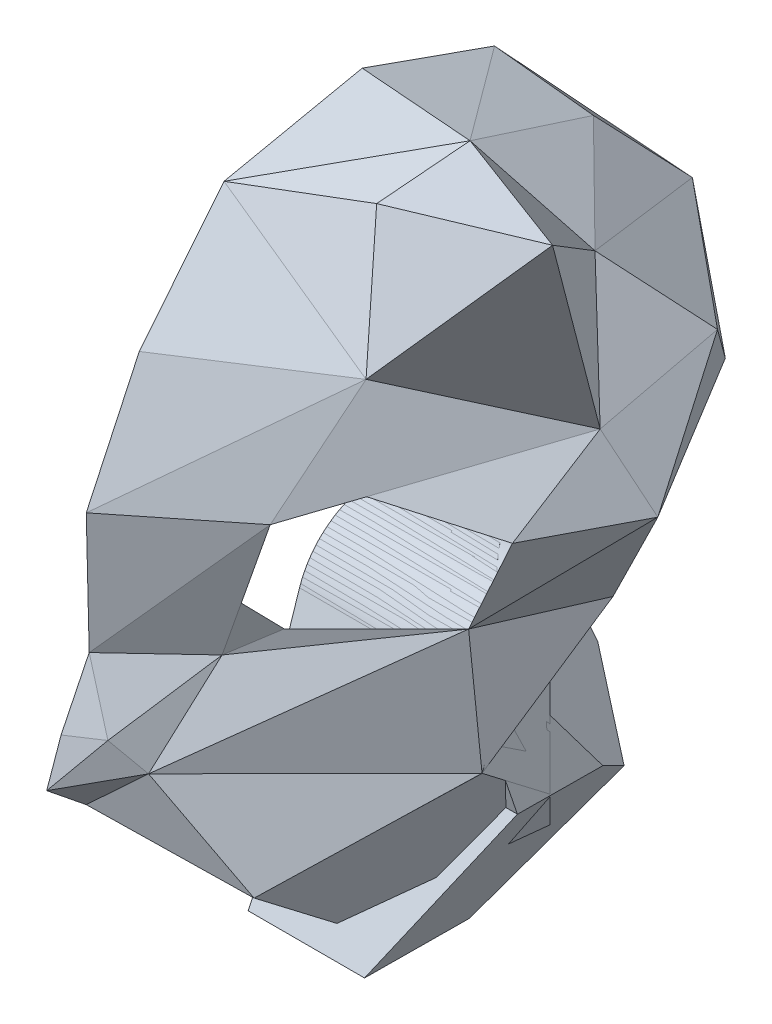
SolidWorks part; units mm, degrees
ref_plane "Front Plane" through (0, 0, 0) normal (0, 0, 1) x (1, 0, 0)
ref_plane "Top Plane" through (0, 0, 0) normal (0, 1, 0) x (1, 0, 0)
ref_plane "Right Plane" through (0, 0, 0) normal (1, 0, 0) x (0, 0, -1)
sketch "Front Pic" plane through (0, 0, 0) normal (0, 0, 1) x (1, 0, 0)
  line L0 (0, -457.2) -> (0, 457.2) construction
  line L1 (-457.2, 0) -> (457.2, 0) construction
  line L2 (-354.5768, -128.31) -> (79.4232, -128.31) construction
  point P4 (0, 0)
  point P8 (0, 0)
  dimension "D1" = 914.4
sketch "Front Sketch" plane through (0, 0, 0) normal (0, 0, 1) x (1, 0, 0)
  line L0 (0, 457.2) -> (-165.0753, 450.1039)
  line L1 (-165.0753, 450.1039) -> (-138.2224, 411.8242)
  line L2 (-138.2224, 411.8242) -> (-198.7843, 255.8487)
  line L3 (-198.7843, 255.8487) -> (-429.6051, 520.3785)
  line L4 (-429.6051, 520.3785) -> (-138.2224, 411.8242)
  line L5 (0, 457.2) -> (0, 259.8481)
  line L6 (0, -457.2) -> (0, 457.2) construction
  line L7 (0, 259.8481) -> (-198.7843, 255.8487)
  line L8 (-138.2224, 411.8242) -> (0, 414.6051)
  line L9 (-429.6051, 520.3785) -> (-381.0413, 202.1428)
  line L10 (-381.0413, 202.1428) -> (-198.7843, 255.8487)
  line L11 (-198.7843, 255.8487) -> (-150.7692, 92.9039)
  line L12 (-150.7692, 92.9039) -> (150.7692, 92.9039)
  line L13 (0, 92.9039) -> (0, 259.8481)
  line L14 (-150.7692, 92.9039) -> (-96.0877, -92.6643)
  line L15 (-96.0877, -92.6643) -> (0, -87.6822)
  line L16 (0, -87.6822) -> (0, 92.9039)
  line L17 (-150.7692, 92.9039) -> (-381.0413, 202.1428)
  line L18 (-381.0413, 202.1428) -> (-347.0618, 86.8295)
  line L19 (-347.0618, 86.8295) -> (-218.0815, 124.8362)
  line L20 (-347.0618, 86.8295) -> (-434.9799, 101.0648)
  line L21 (-434.9799, 101.0648) -> (-325.7476, -76.4377)
  line L22 (-325.7476, -76.4377) -> (-282.294, -55.0183)
  line L23 (-282.294, -55.0183) -> (-347.0618, 86.8295)
  line L24 (-325.7476, -76.4377) -> (-294.3404, -236.9902)
  line L25 (-294.3404, -236.9902) -> (-282.294, -55.0183)
  line L26 (-282.294, -55.0183) -> (-143.2329, -58.0087)
  line L27 (-143.2329, -58.0087) -> (-96.0877, -92.6643)
  line L28 (-71.7002, -214.569) -> (-282.294, -55.0183)
  line L29 (-143.2329, -58.0087) -> (-117.9524, -18.4637)
  line L30 (-96.0877, -92.6643) -> (0, -232.6592)
  line L31 (0, -232.6592) -> (0, -87.6822)
  line L32 (0, -232.6592) -> (0, -279.6939)
  line L33 (0, -279.6939) -> (-71.7002, -214.569)
  line L34 (-71.7002, -214.569) -> (-41.5067, -172.186)
  line L35 (-41.5067, -172.186) -> (41.5067, -172.186)
  line L36 (-71.7002, -214.569) -> (-294.3404, -236.9902)
  line L37 (-294.3404, -236.9902) -> (-172.0864, -350.6598)
  line L38 (-172.0864, -350.6598) -> (172.0864, -350.6598)
  line L39 (0, -350.6598) -> (0, -279.6939)
  line L40 (-434.9799, 101.0648) -> (-381.0413, 202.1428)
  line L41 (381.0413, 202.1428) -> (325.7476, 378.1651)
  line L42 (-143.2329, -350.6598) -> (-89.5204, -431.353)
  line L43 (-89.5204, -431.353) -> (89.5204, -431.353)
  line L44 (0, -431.353) -> (0, -350.6598)
  line L45 (-76.301, -431.353) -> (-51.5863, -391.0064)
  line L46 (-51.5863, -391.0064) -> (-37.7921, -431.353)
  line L47 (-117.9524, -350.6598) -> (-86.0432, -402.0403)
  line L48 (-86.0432, -402.0403) -> (-71.7002, -350.6598)
  line L49 (-233.2134, -293.825) -> (-122.2817, -456.0677)
  line L50 (-122.2817, -456.0677) -> (122.2817, -456.0677)
  line L51 (0, -456.0677) -> (0, -431.353)
  line L52 (233.2134, -293.825) -> (122.2817, -456.0677)
  line L53 (86.0432, -402.0403) -> (71.7002, -350.6598)
  line L54 (117.9524, -350.6598) -> (86.0432, -402.0403)
  line L55 (51.5863, -391.0064) -> (37.7921, -431.353)
  line L56 (76.301, -431.353) -> (51.5863, -391.0064)
  line L57 (143.2329, -350.6598) -> (89.5204, -431.353)
  line L58 (325.7476, 378.1651) -> (138.2224, 411.8242)
  line L59 (434.9799, 101.0648) -> (381.0413, 202.1428)
  line L60 (294.3404, -236.9902) -> (172.0864, -350.6598)
  line L61 (71.7002, -214.569) -> (294.3404, -236.9902)
  line L62 (71.7002, -214.569) -> (41.5067, -172.186)
  line L63 (0, -279.6939) -> (71.7002, -214.569)
  line L64 (96.0877, -92.6643) -> (0, -232.6592)
  line L65 (143.2329, -58.0087) -> (117.9524, -18.4637)
  line L66 (0, -456.0677) -> (89.5204, -431.353)
  line L67 (143.2329, -58.0087) -> (96.0877, -92.6643)
  line L68 (282.294, -55.0183) -> (143.2329, -58.0087)
  line L69 (294.3404, -236.9902) -> (282.294, -55.0183)
  line L70 (325.7476, -76.4377) -> (294.3404, -236.9902)
  line L71 (282.294, -55.0183) -> (347.0618, 86.8295)
  line L72 (325.7476, -76.4377) -> (282.294, -55.0183)
  line L73 (434.9799, 101.0648) -> (325.7476, -76.4377)
  line L74 (347.0618, 86.8295) -> (434.9799, 101.0648)
  line L75 (347.0618, 86.8295) -> (218.0815, 124.8362)
  line L76 (381.0413, 202.1428) -> (347.0618, 86.8295)
  line L77 (150.7692, 92.9039) -> (381.0413, 202.1428)
  line L78 (96.0877, -92.6643) -> (0, -87.6822)
  line L79 (150.7692, 92.9039) -> (96.0877, -92.6643)
  line L80 (198.7843, 255.8487) -> (150.7692, 92.9039)
  line L81 (381.0413, 202.1428) -> (198.7843, 255.8487)
  line L82 (429.6051, 520.3785) -> (381.0413, 202.1428)
  line L83 (138.2224, 411.8242) -> (0, 414.6051)
  line L84 (0, 259.8481) -> (198.7843, 255.8487)
  line L85 (429.6051, 520.3785) -> (138.2224, 411.8242)
  line L86 (198.7843, 255.8487) -> (429.6051, 520.3785)
  line L87 (138.2224, 411.8242) -> (198.7843, 255.8487)
  line L88 (165.0753, 450.1039) -> (138.2224, 411.8242)
  line L89 (0, 457.2) -> (165.0753, 450.1039)
  line L90 (-172.0864, -350.6598) -> (-71.7002, -214.569)
  line L91 (172.0864, -350.6598) -> (71.7002, -214.569)
  line L92 (-172.0864, -350.6598) -> (0, -279.6939)
  line L93 (-71.7002, -214.569) -> (-96.0877, -92.6643)
  line L94 (-96.0877, -92.6643) -> (-282.294, -55.0183)
  line L95 (0, -87.6822) -> (-150.7692, 92.9039)
  line L96 (0, 92.9039) -> (-198.7843, 255.8487)
  line L97 (-198.7843, 255.8487) -> (0, 414.6051)
  line L98 (0, 414.6051) -> (-165.0753, 450.1039)
  line L99 (-122.2817, -456.0677) -> (-89.5204, -431.353)
  line L100 (0, -456.0677) -> (-89.5204, -431.353)
  line L101 (-282.294, -55.0183) -> (-434.9799, 101.0648)
  line L102 (122.2817, -456.0677) -> (89.5204, -431.353)
  line L103 (282.294, -55.0183) -> (434.9799, 101.0648)
  line L104 (0, 414.6051) -> (165.0753, 450.1039)
  line L105 (198.7843, 255.8487) -> (0, 414.6051)
  line L106 (0, 92.9039) -> (198.7843, 255.8487)
  line L107 (0, -87.6822) -> (150.7692, 92.9039)
  line L108 (71.7002, -214.569) -> (96.0877, -92.6643)
  line L109 (96.0877, -92.6643) -> (282.294, -55.0183)
  line L110 (71.7002, -214.569) -> (282.294, -55.0183)
  line L111 (172.0864, -350.6598) -> (0, -279.6939)
  line L112 (-41.5067, -172.186) -> (0, -87.6822)
  line L113 (41.5067, -172.186) -> (0, -87.6822)
  line L114 (165.0753, 450.1039) -> (325.7476, 378.1651)
  line L115 (325.7476, 378.1651) -> (429.6051, 520.3785)
  line L116 (434.9799, 101.0648) -> (413.843, 275.5952)
  line L117 (413.843, 275.5952) -> (325.7476, 378.1651)
  line L118 (-434.9799, 101.0648) -> (-413.843, 275.5952)
  line L119 (-381.0413, 202.1428) -> (-325.7476, 378.1651)
  line L120 (-413.843, 275.5952) -> (-325.7476, 378.1651)
  line L121 (-325.7476, 378.1651) -> (-429.6051, 520.3785)
  line L122 (-165.0753, 450.1039) -> (-325.7476, 378.1651)
  line L123 (-325.7476, 378.1651) -> (-138.2224, 411.8242)
  point P60 (0, -172.186)
sketch "Side Pic" plane through (0, 0, 0) normal (1, 0, 0) x (0, 0, -1)
  line L0 (0, 0) -> (914.4, 0) construction
  line L2 (457.2, -457.2) -> (457.2, 457.2) construction
  line L3 (-402.7911, -837.6232) -> (-658.6062, -472.2814) construction
  point P4 (0, 0)
  point P8 (0, 0)
  point P9 (457.2, 0)
  dimension "D1" = 914.4
sketch "Side Sketch" plane through (0, 0, 0) normal (1, 0, 0) x (0, 0, -1)
  line L0 (0, -232.6592) -> (69.2409, -232.6592) construction
  line L1 (0, -456.0677) -> (498.8433, -456.0677) construction
  line L2 (0, 457.2) -> (534.3463, 457.2) construction
  line L3 (0, -87.6822) -> (131.8928, -87.6822) construction
  line L4 (0, -172.186) -> (90.4589, -172.186) construction
  line L5 (0, 520.3785) -> (0, 202.1428) construction
  line L6 (0, 520.3785) -> (383.7972, 520.3785) construction
  line L7 (69.2409, -232.6592) -> (90.4589, -189.1486)
  line L8 (90.4589, -189.1486) -> (118.3042, -186.9118)
  line L9 (118.3042, -186.9118) -> (148.2945, -199.1583)
  line L10 (148.2945, -199.1583) -> (127.5652, -272.936)
  line L11 (127.5652, -272.936) -> (69.2409, -232.6592)
  line L12 (69.2409, -232.6592) -> (118.3042, -186.9118)
  line L13 (90.4589, -189.1486) -> (131.8928, -87.6822)
  line L14 (131.8928, -87.6822) -> (232.8093, -58.1657)
  line L15 (232.8093, -58.1657) -> (118.3042, -186.9118)
  line L16 (148.2945, -199.1583) -> (290.6522, -152.5117)
  line L17 (290.6522, -152.5117) -> (232.8093, -58.1657)
  line L18 (232.8093, -58.1657) -> (277.7966, -16.2187)
  line L19 (277.7966, -16.2187) -> (237.7872, 11.4104)
  line L20 (237.7872, 11.4104) -> (232.8093, -58.1657)
  line L21 (277.7966, -16.2187) -> (408.2382, 38.4623)
  line L22 (408.2382, 38.4623) -> (290.6522, -152.5117)
  line L23 (127.5652, -272.936) -> (206.0473, -321.2589)
  line L24 (206.0473, -321.2589) -> (290.6522, -152.5117)
  line L25 (206.0473, -321.2589) -> (414.9631, -214.8375)
  line L26 (414.9631, -214.8375) -> (290.6522, -152.5117)
  line L27 (290.6522, -152.5117) -> (576.9901, -43.4043)
  line L28 (576.9901, -43.4043) -> (408.2382, 38.4623)
  line L29 (414.9631, -214.8375) -> (378.4644, -119.0513)
  line L30 (408.2382, 38.4623) -> (534.3463, 67.7772)
  line L31 (534.3463, 67.7772) -> (576.9901, -43.4043)
  line L32 (576.9901, -43.4043) -> (757.3012, -1.4894)
  line L33 (757.3012, -1.4894) -> (712.1006, 116.3584)
  line L34 (712.1006, 116.3584) -> (534.3463, 67.7772)
  line L35 (408.2382, 38.4623) -> (414.9454, 182.3846)
  line L36 (414.9454, 182.3846) -> (543.3881, 217.4886)
  line L37 (543.3881, 217.4886) -> (534.3463, 67.7772)
  line L38 (543.3881, 217.4886) -> (662.4014, 250.0155)
  line L39 (662.4014, 250.0155) -> (712.1006, 116.3584)
  line L40 (131.8928, -87.6822) -> (127.5652, 100.5606)
  line L41 (127.5652, 100.5606) -> (246.365, 119.1618)
  line L42 (246.365, 119.1618) -> (237.7872, 11.4104)
  line L43 (246.365, 119.1618) -> (414.9454, 182.3846)
  line L44 (127.5652, 100.5606) -> (205.7326, 268.0226)
  line L45 (205.7326, 268.0226) -> (348.6096, 307.0716)
  line L46 (348.6096, 307.0716) -> (246.365, 119.1618)
  line L47 (348.6096, 307.0716) -> (514.6158, 303.4287)
  line L48 (514.6158, 303.4287) -> (414.9454, 182.3846)
  line L49 (514.6158, 303.4287) -> (543.3881, 217.4886)
  line L50 (348.6096, 307.0716) -> (389.1511, 552.8335)
  line L51 (389.1511, 552.8335) -> (514.6158, 303.4287)
  line L52 (389.1511, 552.8335) -> (542.7457, 412.354)
  line L53 (542.7457, 412.354) -> (514.6158, 303.4287)
  line L54 (205.7326, 268.0226) -> (330.6552, 382.162)
  line L55 (330.6552, 382.162) -> (535.2557, 438.0803)
  line L56 (535.2557, 438.0803) -> (729.4762, 387.923)
  line L57 (729.4762, 387.923) -> (839.4583, 267.5505)
  line L58 (839.4583, 267.5505) -> (899.1052, 49.3073)
  line L59 (899.1052, 49.3073) -> (817.8739, -176.5412)
  line L60 (817.8739, -176.5412) -> (757.3012, -1.4894)
  line L61 (757.3012, -1.4894) -> (899.1052, 49.3073)
  line L62 (712.1006, 116.3584) -> (839.4583, 267.5505)
  line L63 (662.4014, 250.0155) -> (729.4762, 387.923)
  line L64 (662.4014, 250.0155) -> (542.7457, 412.354)
  line L65 (535.2557, 438.0803) -> (542.7457, 412.354)
  line L66 (310.6236, -412.4283) -> (498.8433, -456.0677)
  line L67 (498.8433, -456.0677) -> (378.4371, -272.936)
  line L68 (378.4371, -272.936) -> (310.6236, -412.4283)
  line L69 (326.9151, -378.9167) -> (311.5844, -355.5994)
  line L70 (311.5844, -355.5994) -> (338.2507, -355.5994)
  line L71 (338.2507, -355.5994) -> (311.5844, -355.5994)
  line L72 (333.9229, -364.5018) -> (311.5844, -355.5994)
  line L73 (228.6505, -309.7449) -> (277.912, -333.6931)
  line L74 (277.912, -333.6931) -> (263.0553, -292.2191)
  line L75 (498.8433, -456.0677) -> (715.2749, -239.6361)
  line L76 (715.2749, -239.6361) -> (681.7952, -214.8729)
  line L77 (681.7952, -214.8729) -> (378.4371, -272.936)
  line L78 (378.4371, -272.936) -> (464.7398, -119.0617)
  line L79 (817.8739, -176.5412) -> (701.6912, -220.2478)
  line L80 (701.6912, -220.2478) -> (576.9901, -43.4043)
  line L81 (0, 92.9039) -> (127.5652, 92.9039) construction
  line L82 (0, 259.8481) -> (205.7326, 259.8481) construction
  line L83 (0, 414.6051) -> (330.6552, 414.6051) construction
  line L84 (0, -279.6939) -> (127.5652, -279.6939) construction
  line L85 (0, -350.6598) -> (202.8829, -350.6598) construction
  arc A0 (464.7398, -119.0617) -> (681.7952, -214.8729) centre (559.3389, -198.5218) cw
ref_plane "Plane1" through (434.9799, 0, 0) normal (1, 0, 0) x (0, 0, -1)
ref_plane "Plane1.5" through (413.843, 0, 0) normal (1, 0, 0) x (0, 0, -1)
ref_plane "Plane2" through (429.6051, 0, 0) normal (1, 0, 0) x (0, 0, -1)
ref_plane "Plane3" through (381.0413, 0, 0) normal (1, 0, 0) x (0, 0, -1)
ref_plane "Plane4" through (325.7476, 0, 0) normal (1, 0, 0) x (0, 0, -1)
ref_plane "Plane5" through (347.0618, 0, 0) normal (1, 0, 0) x (0, 0, -1)
ref_plane "Plane6" through (325.7476, 0, 0) normal (1, 0, 0) x (0, 0, -1)
ref_plane "Plane7" through (294.3404, 0, 0) normal (1, 0, 0) x (0, 0, -1)
ref_plane "Plane8" through (282.294, 0, 0) normal (1, 0, 0) x (0, 0, -1)
ref_plane "Plane9" through (218.0815, 0, 0) normal (1, 0, 0) x (0, 0, -1)
ref_plane "Plane10" through (198.7843, 0, 0) normal (1, 0, 0) x (0, 0, -1)
ref_plane "Plane11" through (172.0864, 0, 0) normal (1, 0, 0) x (0, 0, -1)
ref_plane "Plane12" through (165.0753, 0, 0) normal (1, 0, 0) x (0, 0, -1)
ref_plane "Plane13" through (150.7692, 0, 0) normal (1, 0, 0) x (0, 0, -1)
ref_plane "Plane14" through (143.2329, 0, 0) normal (1, 0, 0) x (0, 0, -1)
ref_plane "Plane14.5" through (138.2224, 0, 0) normal (1, 0, 0) x (0, 0, -1)
ref_plane "Plane15" through (117.9524, 0, 0) normal (1, 0, 0) x (0, 0, -1)
ref_plane "Plane16" through (96.0877, 0, 0) normal (1, 0, 0) x (0, 0, -1)
ref_plane "Plane17" through (86.0432, 0, 0) normal (1, 0, 0) x (0, 0, -1)
ref_plane "Plane18" through (71.7002, 0, 0) normal (1, 0, 0) x (0, 0, -1)
ref_plane "Plane19" through (41.5067, 0, 0) normal (1, 0, 0) x (0, 0, -1)
sketch "P1 Sketch1" plane through (434.9799, 0, 0) normal (1, 0, 0) x (0, 0, -1)
  line L0 (0, 101.0648) -> (535.1548, 101.0648) construction
sketch "P1.5 Sketch2" plane through (413.843, 0, 0) normal (1, 0, 0) x (0, 0, -1)
  line L0 (0, 275.5952) -> (644.2965, 275.5952) construction
sketch "P2 Sketch2" plane through (429.6051, 0, 0) normal (1, 0, 0) x (0, 0, -1)
  line L0 (0, 520.3785) -> (385.3981, 520.3785) construction
  line L1 (0, 520.3785) -> (383.7972, 520.3785) construction
sketch "P3 Sketch3" plane through (381.0413, 0, 0) normal (1, 0, 0) x (0, 0, -1)
  line L0 (0, 202.1428) -> (504.1067, 202.1428) construction
sketch "P4 Sketch4" plane through (325.7476, 0, 0) normal (1, 0, 0) x (0, 0, -1)
  line L0 (0, 378.1651) -> (551.8238, 378.1651) construction
sketch "P5 Sketch5" plane through (347.0618, 0, 0) normal (1, 0, 0) x (0, 0, -1)
  line L0 (0, 86.8295) -> (408.8118, 86.8295) construction
sketch "P6 Sketch6" plane through (325.7476, 0, 0) normal (1, 0, 0) x (0, 0, -1)
  line L0 (0, -76.4377) -> (578.2694, -76.4377) construction
sketch "P7 Sketch7" plane through (294.3404, 0, 0) normal (1, 0, 0) x (0, 0, -1)
  line L0 (0, -236.9902) -> (416.6891, -236.9902) construction
sketch "P8 Sketch8" plane through (282.294, 0, 0) normal (1, 0, 0) x (0, 0, -1)
  line L0 (0, -55.0183) -> (408.9035, -55.0183) construction
sketch "P9 Sketch9" plane through (218.0815, 0, 0) normal (1, 0, 0) x (0, 0, -1)
  line L0 (0, 124.8362) -> (322.7943, 124.8362) construction
sketch "P10 Sketch10" plane through (198.7843, 0, 0) normal (1, 0, 0) x (0, 0, -1)
  line L0 (0, 255.8487) -> (341.2394, 255.8487) construction
sketch "P11 Sketch11" plane through (172.0864, 0, 0) normal (1, 0, 0) x (0, 0, -1)
  line L0 (0, -350.6598) -> (202.8922, -350.6598) construction
sketch "P12 Sketch12" plane through (165.0753, 0, 0) normal (1, 0, 0) x (0, 0, -1)
  line L0 (0, 450.1039) -> (528.2885, 450.1039) construction
sketch "P13 Sketch13" plane through (150.7692, 0, 0) normal (1, 0, 0) x (0, 0, -1)
  line L0 (0, 92.9039) -> (247.9012, 92.9039) construction
sketch "P14 Sketch14" plane through (143.2329, 0, 0) normal (1, 0, 0) x (0, 0, -1)
  line L0 (0, -58.0087) -> (276.2421, -58.0087) construction
sketch "P14.5 Sketch21" plane through (138.2224, 0, 0) normal (1, 0, 0) x (0, 0, -1)
  line L0 (0, 411.8242) -> (417.4757, 411.8242) construction
sketch "P15 Sketch16" plane through (117.9524, 0, 0) normal (1, 0, 0) x (0, 0, -1)
  line L0 (0, -18.4637) -> (237.5826, -18.4637) construction
sketch "P16 Sketch17" plane through (96.0877, 0, 0) normal (1, 0, 0) x (0, 0, -1)
  line L0 (0, -92.6643) -> (231.7277, -92.6643) construction
sketch "P17 Sketch18" plane through (86.0432, 0, 0) normal (1, 0, 0) x (0, 0, -1)
  line L0 (0, -402.0403) -> (279.5869, -402.0403) construction
sketch "P18 Sketch19" plane through (71.7002, 0, 0) normal (1, 0, 0) x (0, 0, -1)
  line L0 (0, -214.569) -> (147.6774, -214.569) construction
sketch "P19 Sketch20" plane through (41.5067, 0, 0) normal (1, 0, 0) x (0, 0, -1)
  line L0 (0, -172.186) -> (117.9153, -172.186) construction
sketch3d "3DSketch1"
  line L0 (198.7843, 255.8487, -341.2394) -> (381.0413, 202.1428, -504.1067)
  line L1 (381.0413, 202.1428, -504.1067) -> (429.6051, 520.3785, -385.3981)
  line L2 (429.6051, 520.3785, -385.3981) -> (198.7843, 255.8487, -341.2394)
sketch3d "3DSketch3"
  line L0 (198.7843, 255.8487, -341.2394) -> (138.2224, 411.8242, -417.4757)
  line L1 (138.2224, 411.8242, -417.4757) -> (429.6051, 520.3785, -385.3981)
  line L2 (429.6051, 520.3785, -385.3981) -> (198.7843, 255.8487, -341.2394)
sketch3d "3DSketch4"
  line L0 (138.2224, 411.8242, -417.4757) -> (0, 414.6051, -330.6552)
  line L3 (165.0753, 450.1039, -528.2885) -> (138.2224, 411.8242, -417.4757)
  line L4 (0, 414.6051, -330.6552) -> (165.0753, 450.1039, -528.2885)
sketch3d "3DSketch5"
  line L2 (0, 414.6051, -330.6552) -> (138.2224, 411.8242, -417.4757)
  line L3 (138.2224, 411.8242, -417.4757) -> (198.7843, 255.8487, -341.2394)
  line L4 (198.7843, 255.8487, -341.2394) -> (0, 414.6051, -330.6552)
sketch3d "3DSketch6"
  line L2 (198.7843, 255.8487, -341.2394) -> (150.7692, 92.9039, -247.9012)
  line L3 (150.7692, 92.9039, -247.9012) -> (0, 92.9039, -127.5652)
  line L4 (0, 92.9039, -127.5652) -> (198.7843, 255.8487, -341.2394)
sketch3d "3DSketch7"
  line L0 (347.0618, 86.8295, -408.8118) -> (381.0413, 202.1428, -504.1067)
  line L1 (381.0413, 202.1428, -504.1067) -> (218.0815, 124.8362, -322.7943)
  line L2 (218.0815, 124.8362, -322.7943) -> (347.0618, 86.8295, -408.8118)
sketch3d "3DSketch8"
  line L0 (150.7692, 92.9039, -247.9012) -> (381.0413, 202.1428, -504.1067)
  line L1 (381.0413, 202.1428, -504.1067) -> (198.7843, 255.8487, -341.2394)
  line L2 (198.7843, 255.8487, -341.2394) -> (150.7692, 92.9039, -247.9012)
surface "Surface-Fill1" sketch "3DSketch1"
surface "Surface-Fill2" sketch "3DSketch3"
surface "Surface-Fill6" sketch "3DSketch7"
surface "Surface-Fill7" sketch "3DSketch8"
sketch3d "3DSketch11"
  line L0 (96.0877, -92.6643, -231.7277) -> (143.2329, -58.0087, -276.2421)
  line L1 (143.2329, -58.0087, -276.2421) -> (282.294, -55.0183, -408.9035)
  line L4 (96.0877, -92.6643, -231.7277) -> (282.294, -55.0183, -408.9035)
sketch3d "3DSketch12"
  line L1 (96.0877, -92.6643, -231.7277) -> (41.5067, -172.186, -117.9153)
  line L2 (41.5067, -172.186, -117.9153) -> (71.7002, -214.569, -147.6774)
  line L4 (71.7002, -214.569, -147.6774) -> (96.0877, -92.6643, -231.7277)
sketch3d "3DSketch13"
  line L0 (0, -172.186, -90.4589) -> (0, -87.6822, -131.8928)
  line L3 (41.5067, -172.186, -117.9153) -> (0, -172.186, -90.4589)
  line L4 (41.5067, -172.186, -117.9153) -> (0, -87.6822, -131.8928)
sketch3d "3DSketch14"
  line L3 (0, -232.6592, -69.2409) -> (0, -172.186, -90.4589)
  line L4 (0, -172.186, -90.4589) -> (41.5067, -172.186, -117.9153)
  line L5 (41.5067, -172.186, -117.9153) -> (0, -232.6592, -69.2409)
surface "Surface-Fill13" sketch "3DSketch14"
sketch3d "3DSketch15"
  line L0 (41.5067, -172.186, -117.9153) -> (71.7002, -214.569, -147.6774)
  line L1 (71.7002, -214.569, -147.6774) -> (0, -232.6592, -69.2409)
  line L2 (0, -232.6592, -69.2409) -> (41.5067, -172.186, -117.9153)
surface "Surface-Fill14" sketch "3DSketch15"
sketch3d "3DSketch16"
  line L0 (71.7002, -214.569, -147.6774) -> (0, -279.6939, -127.5652)
  line L1 (0, -279.6939, -127.5652) -> (0, -232.6592, -69.2409)
  line L2 (0, -232.6592, -69.2409) -> (71.7002, -214.569, -147.6774)
surface "Surface-Fill15" sketch "3DSketch16"
sketch3d "3DSketch18"
  line L1 (172.0864, -350.6598, -202.8922) -> (71.7002, -214.569, -147.6774)
  line L2 (71.7002, -214.569, 0) -> (71.7002, -214.569, -147.6774) construction
  line L3 (0, -232.6592, -69.2409) -> (71.7002, -214.569, -147.6774) construction
  line L4 (71.7002, -214.569, -147.6774) -> (0, -279.6939, -127.5652)
  line L6 (172.0864, -350.6598, -202.8922) -> (0, -279.6939, -127.5652)
sketch3d "3DSketch19"
  line L0 (172.0864, -350.6598, -202.8922) -> (294.3404, -236.9902, -416.6891)
  line L1 (172.0864, -350.6598, 0) -> (172.0864, -350.6598, -202.8922) construction
  line L3 (294.3404, -236.9902, -416.6891) -> (71.7002, -214.569, -147.6774)
  line L4 (71.7002, -214.569, -147.6774) -> (172.0864, -350.6598, -202.8922)
surface "Surface-Fill17" sketch "3DSketch19"
sketch3d "3DSketch20"
  line L0 (294.3404, -236.9902, -416.6891) -> (325.7476, -76.4377, -578.2694)
  line L1 (325.7476, -76.4377, -578.2694) -> (282.294, -55.0183, -408.9035)
  line L2 (282.294, -55.0183, -408.9035) -> (294.3404, -236.9902, -416.6891)
surface "Surface-Fill18" sketch "3DSketch20"
sketch3d "3DSketch21"
  line L1 (282.294, -55.0183, -408.9035) -> (347.0618, 86.8295, -408.8118)
  line L2 (347.0618, 86.8295, -408.8118) -> (434.9799, 101.0648, -535.1548)
  line L4 (282.294, -55.0183, -408.9035) -> (434.9799, 101.0648, -535.1548)
surface "Surface-Fill19" sketch "3DSketch21"
sketch3d "3DSketch22"
  line L0 (282.294, -55.0183, -408.9035) -> (325.7476, -76.4377, -578.2694)
  line L1 (325.7476, -76.4377, -578.2694) -> (434.9799, 101.0648, -535.1548)
  line L2 (434.9799, 101.0648, -535.1548) -> (282.294, -55.0183, -408.9035)
surface "Surface-Fill20" sketch "3DSketch22"
surface "Surface-Fill21" sketch "3DSketch18"
sketch3d "3DSketch23"
  line L0 (172.0864, -350.6598, -202.8922) -> (0, -350.6598, -202.8829)
  line L1 (0, -350.6598, -202.8829) -> (0, -279.6939, -127.5652)
  line L2 (0, -279.6939, -127.5652) -> (172.0864, -350.6598, -202.8922)
surface "Surface-Fill22" sketch "3DSketch23"
surface "Surface-Fill23" sketch "3DSketch13"
sketch3d "3DSketch24"
  line L0 (41.5067, -172.186, -117.9153) -> (0, -87.6822, -131.8928)
  line L1 (0, -87.6822, -131.8928) -> (96.0877, -92.6643, -231.7277)
  line L2 (96.0877, -92.6643, -231.7277) -> (41.5067, -172.186, -117.9153)
surface "Surface-Fill24" sketch "3DSketch24"
surface "Surface-Fill25" sketch "3DSketch12"
surface "Surface-Fill26" sketch "3DSketch11"
sketch3d "3DSketch25"
  line L0 (71.7002, -214.569, -147.6774) -> (282.294, -55.0183, -408.9035)
  line L1 (282.294, -55.0183, -408.9035) -> (96.0877, -92.6643, -231.7277)
  line L2 (96.0877, -92.6643, -231.7277) -> (71.7002, -214.569, -147.6774)
surface "Surface-Fill27" sketch "3DSketch25"
sketch3d "3DSketch26"
  line L0 (71.7002, -214.569, -147.6774) -> (294.3404, -236.9902, -416.6891)
  line L1 (294.3404, -236.9902, -416.6891) -> (282.294, -55.0183, -408.9035)
  line L2 (282.294, -55.0183, -408.9035) -> (71.7002, -214.569, -147.6774)
surface "Surface-Fill28" sketch "3DSketch26"
sketch3d "3DSketch27"
  line L0 (434.9799, 101.0648, -535.1548) -> (381.0413, 202.1428, -504.1067)
  line L1 (381.0413, 202.1428, -504.1067) -> (347.0618, 86.8295, -408.8118)
  line L2 (347.0618, 86.8295, -408.8118) -> (434.9799, 101.0648, -535.1548)
surface "Surface-Fill29" sketch "3DSketch27"
sketch3d "3DSketch29"
  line L0 (0, -87.6822, -131.8928) -> (150.7692, 92.9039, -247.9012)
  line L1 (150.7692, 92.9039, -247.9012) -> (96.0877, -92.6643, -231.7277)
  line L2 (96.0877, -92.6643, -231.7277) -> (0, -87.6822, -131.8928)
surface "Surface-Fill34" sketch "3DSketch29"
sketch3d "3DSketch30"
  line L0 (96.0877, -92.6643, -231.7277) -> (143.2329, -58.0087, -276.2421)
  line L1 (143.2329, -58.0087, -276.2421) -> (117.8744, -18.7283, -238.1717)
  line L2 (150.7692, 92.9039, -247.9012) -> (96.0877, -92.6643, -231.7277) construction
  line L3 (117.8744, -18.7283, -238.1717) -> (96.0877, -92.6643, -231.7277)
surface "Surface-Fill35" sketch "3DSketch30"
sketch3d "3DSketch31"
  line L0 (0, -87.6822, -131.8928) -> (150.7692, 92.9039, -247.9012)
  line L1 (150.7692, 92.9039, -247.9012) -> (0, 92.9039, -127.5652)
  line L2 (0, 92.9039, -127.5652) -> (0, -87.6822, -131.8928)
surface "Surface-Fill36" sketch "3DSketch31"
surface "Surface-Fill37" sketch "3DSketch6"
sketch3d "3DSketch32"
  line L0 (0, 92.9039, -127.5652) -> (0, 259.8481, -205.7326)
  line L1 (0, 259.8481, -205.7326) -> (198.7843, 255.8487, -341.2394)
  line L2 (198.7843, 255.8487, -341.2394) -> (0, 92.9039, -127.5652)
surface "Surface-Fill38" sketch "3DSketch32"
surface "Surface-Fill39" sketch "3DSketch5"
sketch3d "3DSketch33"
  line L0 (0, 259.8481, -205.7326) -> (0, 414.6051, -330.6552)
  line L1 (0, 414.6051, -330.6552) -> (198.7843, 255.8487, -341.2394)
  line L2 (198.7843, 255.8487, -341.2394) -> (0, 259.8481, -205.7326)
surface "Surface-Fill40" sketch "3DSketch33"
surface "Surface-Fill41" sketch "3DSketch4"
sketch3d "3DSketch34"
  line L0 (0, 414.6051, -330.6552) -> (0, 457.2, -534.3463)
  line L1 (0, 457.2, -534.3463) -> (165.0753, 450.1039, -528.2885)
  line L2 (165.0753, 450.1039, -528.2885) -> (0, 414.6051, -330.6552)
surface "Surface-Fill42" sketch "3DSketch34"
sketch3d "3DSketch35"
  line L0 (165.0753, 450.1039, -528.2885) -> (429.6051, 520.3785, -385.3981)
  line L1 (429.6051, 520.3785, -385.3981) -> (138.2224, 411.8242, -417.4757)
  line L2 (138.2224, 411.8242, -417.4757) -> (165.0753, 450.1039, -528.2885)
surface "Surface-Fill43" sketch "3DSketch35"
sketch3d "3DSketch36"
  line L0 (165.0753, 450.1039, -528.2885) -> (325.7476, 378.1651, -551.8238)
  line L1 (325.7476, 378.1651, -551.8238) -> (429.6051, 520.3785, -385.3981)
  line L2 (429.6051, 520.3785, -385.3981) -> (165.0753, 450.1039, -528.2885)
surface "Surface-Fill44" sketch "3DSketch36"
sketch3d "3DSketch37"
  line L0 (325.7476, 378.1651, -551.8238) -> (429.6051, 520.3785, -385.3981)
  line L1 (429.6051, 520.3785, -385.3981) -> (381.0413, 202.1428, -504.1067)
  line L2 (381.0413, 202.1428, -504.1067) -> (325.7476, 378.1651, -551.8238)
surface "Surface-Fill45" sketch "3DSketch37"
sketch3d "3DSketch38"
  line L0 (434.9799, 101.0648, -535.1548) -> (413.843, 275.5952, -644.2965)
  line L1 (413.843, 275.5952, -644.2965) -> (381.0413, 202.1428, -504.1067)
  line L2 (381.0413, 202.1428, -504.1067) -> (434.9799, 101.0648, -535.1548)
surface "Surface-Fill46" sketch "3DSketch38"
sketch3d "3DSketch39"
  line L0 (413.843, 275.5952, -644.2965) -> (325.7476, 378.1651, -551.8238)
  line L1 (325.7476, 378.1651, -551.8238) -> (381.0413, 202.1428, -504.1067)
  line L2 (381.0413, 202.1428, -504.1067) -> (413.843, 275.5952, -644.2965)
surface "Surface-Fill47" sketch "3DSketch39"
ref_plane "Back Plane" through (0, 0, -1270) normal (0, 0, 1) x (1, 0, 0)
sketch "Back Sketch" plane through (0, 0, -1270) normal (0, 0, 1) x (1, 0, 0)
  line L0 (325.7476, -76.4377) -> (294.3404, -236.9902) construction
  line L1 (434.9799, 101.0648) -> (325.7476, -76.4377) construction
  line L2 (413.843, 275.5952) -> (434.9799, 101.0648) construction
  line L3 (325.7476, 378.1651) -> (413.843, 275.5952) construction
  line L4 (0, 457.2) -> (165.0753, 450.1039) construction
  line L5 (325.7476, 378.1651) -> (165.0753, 450.1039) construction
  line L6 (325.7476, -76.4377) -> (294.3404, -236.9902)
  line L7 (434.9799, 101.0648) -> (325.7476, -76.4377)
  line L8 (413.843, 275.5952) -> (434.9799, 101.0648)
  line L9 (325.7476, 378.1651) -> (413.843, 275.5952)
  line L10 (0, 457.2) -> (165.0753, 450.1039)
  line L11 (325.7476, 378.1651) -> (165.0753, 450.1039)
  line L12 (0, -176.5412) -> (0, -220.2478) construction
  line L13 (0, 49.3073) -> (0, -176.5412) construction
  line L14 (0, 267.5505) -> (0, 49.3073) construction
  line L15 (0, 387.923) -> (0, 267.5505) construction
  line L16 (0, -176.5412) -> (0, -220.2478)
  line L17 (0, 49.3073) -> (0, -176.5412)
  line L18 (0, 267.5505) -> (0, 49.3073)
  line L19 (0, 387.923) -> (0, 267.5505)
  line L20 (0, 457.2) -> (0, 387.923)
  line L21 (165.0753, 450.1039) -> (147.1502, 373.5852)
  line L22 (165.0753, 450.1039) -> (0, 387.923)
  line L23 (147.1502, 373.5852) -> (0, 387.923)
  line L24 (147.1502, 373.5852) -> (325.7476, 378.1651)
  line L25 (147.1502, 373.5852) -> (217.985, 292.2455)
  line L26 (0, 267.5505) -> (147.1502, 373.5852)
  line L27 (217.985, 292.2455) -> (325.7476, 378.1651)
  line L28 (217.985, 292.2455) -> (413.843, 275.5952)
  line L29 (217.985, 292.2455) -> (0, 267.5505)
  line L30 (413.843, 275.5952) -> (309.066, 128.4053)
  line L31 (309.066, 128.4053) -> (434.9799, 101.0648)
  line L32 (309.066, 128.4053) -> (217.985, 292.2455)
  line L33 (309.066, 128.4053) -> (325.7476, -76.4377)
  line L34 (294.3404, -236.9902) -> (190.8328, -232.1413)
  line L35 (190.8328, -232.1413) -> (195.7916, -55.9279)
  line L36 (190.8328, -232.1413) -> (325.7476, -76.4377)
  line L37 (195.7916, -55.9279) -> (325.7476, -76.4377)
  line L38 (309.066, 128.4053) -> (195.7916, -55.9279)
  line L39 (309.066, 128.4053) -> (153.5325, 142.8228)
  line L40 (153.5325, 142.8228) -> (195.7916, -55.9279)
  line L41 (153.5325, 142.8228) -> (217.985, 292.2455)
  line L42 (0, 267.5505) -> (153.5325, 142.8228)
  line L43 (0, 49.3073) -> (153.5325, 142.8228)
  line L44 (0, 49.3073) -> (195.7916, -55.9279)
  line L45 (0, -176.5412) -> (195.7916, -55.9279)
  line L46 (0, -176.5412) -> (190.8328, -232.1413)
ref_plane "Plane22" through (147.1502, 0, 0) normal (1, 0, 0) x (0, 0, -1)
ref_plane "Plane23" through (217.985, 0, 0) normal (1, 0, 0) x (0, 0, -1)
ref_plane "Plane24" through (309.066, 0, 0) normal (1, 0, 0) x (0, 0, -1)
ref_plane "Plane25" through (190.8328, 0, 0) normal (1, 0, 0) x (0, 0, -1)
ref_plane "Plane26" through (195.7916, 0, 0) normal (1, 0, 0) x (0, 0, -1)
ref_plane "Plane27" through (153.5325, 0, 0) normal (1, 0, 0) x (0, 0, -1)
sketch "P22 Sketch" plane through (147.1502, 0, 0) normal (1, 0, 0) x (0, 0, -1)
  line L0 (1270, 373.5852) -> (728.0328, 373.5852) construction
sketch "P23 Sketch" plane through (217.985, 0, 0) normal (1, 0, 0) x (0, 0, -1)
  line L0 (1270, 292.2455) -> (803.0794, 292.2455) construction
sketch "P24 Sketch" plane through (309.066, 0, 0) normal (1, 0, 0) x (0, 0, -1)
  line L0 (1270, 128.4053) -> (760.5631, 128.4053) construction
sketch "P25 Sketch" plane through (190.8328, 0, 0) normal (1, 0, 0) x (0, 0, -1)
  line L0 (1270, -232.1413) -> (673.5887, -232.1413) construction
sketch "P26 Sketch" plane through (195.7916, 0, 0) normal (1, 0, 0) x (0, 0, -1)
  line L0 (1270, -55.9279) -> (799.0116, -55.9279) construction
sketch "P27 Sketch" plane through (153.5325, 0, 0) normal (1, 0, 0) x (0, 0, -1)
  line L0 (1270, 142.8228) -> (856.9576, 142.8228) construction
sketch "Side Sketch From Back" plane through (0, 0, 0) normal (1, 0, 0) x (0, 0, -1)
  line L0 (1270, 387.923) -> (729.4762, 387.923) construction
  line L1 (1270, 267.5505) -> (839.4583, 267.5505) construction
  line L2 (1270, 49.3073) -> (899.1052, 49.3073) construction
  line L3 (1270, -176.5412) -> (817.8739, -176.5412) construction
  line L4 (1270, -220.2478) -> (701.6912, -220.2478) construction
sketch3d "3DSketch40"
  line L0 (0, 457.2, -534.3463) -> (0, 387.923, -729.4762)
  line L1 (0, 387.923, -729.4762) -> (165.0753, 450.1039, -528.2885)
  line L2 (165.0753, 450.1039, -528.2885) -> (0, 457.2, -534.3463)
surface "Surface-Fill48" sketch "3DSketch40"
sketch3d "3DSketch41"
  line L0 (0, 387.923, -729.4762) -> (147.1502, 373.5852, -728.0328)
  line L1 (147.1502, 373.5852, -728.0328) -> (165.0753, 450.1039, -528.2885)
  line L2 (165.0753, 450.1039, -528.2885) -> (0, 387.923, -729.4762)
surface "Surface-Fill49" sketch "3DSketch41"
sketch3d "3DSketch42"
  line L0 (147.1502, 373.5852, -728.0328) -> (325.7476, 378.1651, -551.8238)
  line L1 (325.7476, 378.1651, -551.8238) -> (165.0753, 450.1039, -528.2885)
  line L2 (165.0753, 450.1039, -528.2885) -> (147.1502, 373.5852, -728.0328)
surface "Surface-Fill50" sketch "3DSketch42"
sketch3d "3DSketch43"
  line L0 (217.985, 292.2455, -803.0794) -> (147.1502, 373.5852, -728.0328)
  line L1 (147.1502, 373.5852, -728.0328) -> (325.7476, 378.1651, -551.8238)
  line L2 (325.7476, 378.1651, -551.8238) -> (217.985, 292.2455, -803.0794)
surface "Surface-Fill51" sketch "3DSketch43"
sketch3d "3DSketch44"
  line L0 (217.985, 292.2455, -803.0794) -> (413.843, 275.5952, -644.2965)
  line L1 (413.843, 275.5952, -644.2965) -> (325.7476, 378.1651, -551.8238)
  line L2 (325.7476, 378.1651, -551.8238) -> (217.985, 292.2455, -803.0794)
surface "Surface-Fill52" sketch "3DSketch44"
sketch3d "3DSketch45"
  line L0 (309.066, 128.4053, -760.5631) -> (413.843, 275.5952, -644.2965)
  line L1 (413.843, 275.5952, -644.2965) -> (434.9799, 101.0648, -535.1548)
  line L2 (434.9799, 101.0648, -535.1548) -> (309.066, 128.4053, -760.5631)
surface "Surface-Fill53" sketch "3DSketch45"
sketch3d "3DSketch46"
  line L0 (309.066, 128.4053, -760.5631) -> (325.7476, -76.4377, -578.2694)
  line L1 (325.7476, -76.4377, -578.2694) -> (434.9799, 101.0648, -535.1548)
  line L2 (434.9799, 101.0648, -535.1548) -> (309.066, 128.4053, -760.5631)
surface "Surface-Fill54" sketch "3DSketch46"
sketch3d "3DSketch47"
  line L0 (309.066, 128.4053, -760.5631) -> (217.985, 292.2455, -803.0794)
  line L1 (217.985, 292.2455, -803.0794) -> (413.843, 275.5952, -644.2965)
  line L2 (413.843, 275.5952, -644.2965) -> (309.066, 128.4053, -760.5631)
surface "Surface-Fill55" sketch "3DSketch47"
sketch3d "3DSketch48"
  line L0 (0, 387.923, -729.4762) -> (217.985, 292.2455, -803.0794)
  line L1 (217.985, 292.2455, -803.0794) -> (0, 267.5505, -839.4583)
  line L2 (0, 267.5505, -839.4583) -> (0, 387.923, -729.4762)
surface "Surface-Fill56" sketch "3DSketch48"
sketch3d "3DSketch49"
  line L0 (217.985, 292.2455, -803.0794) -> (0, 387.923, -729.4762)
  line L1 (0, 387.923, -729.4762) -> (147.1502, 373.5852, -728.0328)
  line L2 (147.1502, 373.5852, -728.0328) -> (217.985, 292.2455, -803.0794)
surface "Surface-Fill57" sketch "3DSketch49"
sketch3d "3DSketch50"
  line L0 (190.8328, -232.1413, -673.5887) -> (325.7476, -76.4377, -578.2694)
  line L1 (325.7476, -76.4377, -578.2694) -> (195.7916, -55.9279, -799.0116)
  line L2 (195.7916, -55.9279, -799.0116) -> (190.8328, -232.1413, -673.5887)
surface "Surface-Fill59" sketch "3DSketch50"
sketch3d "3DSketch51"
  line L0 (195.7916, -55.9279, -799.0116) -> (325.7476, -76.4377, -578.2694)
  line L1 (325.7476, -76.4377, -578.2694) -> (309.066, 128.4053, -760.5631)
  line L2 (309.066, 128.4053, -760.5631) -> (195.7916, -55.9279, -799.0116)
surface "Surface-Fill60" sketch "3DSketch51"
sketch3d "3DSketch52"
  line L0 (153.5325, 142.8228, -856.9576) -> (195.7916, -55.9279, -799.0116)
  line L1 (195.7916, -55.9279, -799.0116) -> (309.066, 128.4053, -760.5631)
  line L2 (309.066, 128.4053, -760.5631) -> (153.5325, 142.8228, -856.9576)
surface "Surface-Fill61" sketch "3DSketch52"
sketch3d "3DSketch53"
  line L0 (153.5325, 142.8228, -856.9576) -> (309.066, 128.4053, -760.5631)
  line L1 (309.066, 128.4053, -760.5631) -> (217.985, 292.2455, -803.0794)
  line L2 (217.985, 292.2455, -803.0794) -> (153.5325, 142.8228, -856.9576)
surface "Surface-Fill62" sketch "3DSketch53"
sketch3d "3DSketch54"
  line L0 (153.5325, 142.8228, -856.9576) -> (0, 267.5505, -839.4583)
  line L1 (0, 267.5505, -839.4583) -> (217.985, 292.2455, -803.0794)
  line L2 (217.985, 292.2455, -803.0794) -> (153.5325, 142.8228, -856.9576)
surface "Surface-Fill63" sketch "3DSketch54"
sketch3d "3DSketch55"
  line L0 (0, 267.5505, -839.4583) -> (153.5325, 142.8228, -856.9576)
  line L1 (153.5325, 142.8228, -856.9576) -> (0, 49.3073, -899.1052)
  line L2 (0, 49.3073, -899.1052) -> (0, 267.5505, -839.4583)
surface "Surface-Fill64" sketch "3DSketch55"
sketch3d "3DSketch56"
  line L0 (195.7916, -55.9279, -799.0116) -> (153.5325, 142.8228, -856.9576)
  line L1 (153.5325, 142.8228, -856.9576) -> (0, 49.3073, -899.1052)
  line L2 (0, 49.3073, -899.1052) -> (195.7916, -55.9279, -799.0116)
surface "Surface-Fill65" sketch "3DSketch56"
sketch3d "3DSketch57"
  line L0 (0, -176.5412, -817.8739) -> (195.7916, -55.9279, -799.0116)
  line L1 (195.7916, -55.9279, -799.0116) -> (0, 49.3073, -899.1052)
  line L2 (0, 49.3073, -899.1052) -> (0, -176.5412, -817.8739)
surface "Surface-Fill66" sketch "3DSketch57"
sketch3d "3DSketch58"
  line L0 (0, -176.5412, -817.8739) -> (195.7916, -55.9279, -799.0116)
  line L1 (195.7916, -55.9279, -799.0116) -> (190.8328, -232.1413, -673.5887)
  line L2 (190.8328, -232.1413, -673.5887) -> (0, -176.5412, -817.8739)
surface "Surface-Fill67" sketch "3DSketch58"
sketch "Sketch1" plane through (0, 0, 0) normal (1, 0, 0) x (0, 0, -1)
  line L0 (310.6236, -412.4283) -> (498.8433, -456.0677) construction
  line L1 (310.6236, -412.4283) -> (498.8433, -456.0677)
  line L2 (498.8433, -456.0677) -> (715.2749, -239.6361) construction
  line L3 (715.2749, -239.6361) -> (681.7952, -214.8729) construction
  line L4 (378.4371, -272.936) -> (464.7398, -119.0617) construction
  line L5 (378.4371, -272.936) -> (310.6236, -412.4283) construction
  line L6 (498.8433, -456.0677) -> (715.2749, -239.6361)
  line L7 (715.2749, -239.6361) -> (681.7952, -214.8729)
  line L8 (378.4371, -272.936) -> (464.7398, -119.0617)
  line L9 (378.4371, -272.936) -> (310.6236, -412.4283)
  arc A0 (681.7952, -214.8729) -> (464.7398, -119.0617) centre (559.3389, -198.5218) ccw construction
  arc A1 (681.7952, -214.8729) -> (464.7398, -119.0617) centre (559.3389, -198.5218) ccw
ref_plane "Plane28" through (122.2817, 0, 0) normal (1, 0, 0) x (0, 0, -1)
sketch "P28 Sketch" plane through (122.2817, 0, 0) normal (1, 0, 0) x (0, 0, -1)
  line L0 (0, -456.0677) -> (489.2417, -456.0677) construction
ref_plane "Plane29" through (233.2134, 0, 0) normal (1, 0, 0) x (0, 0, -1)
sketch "P29 Sketch" plane through (233.2134, 0, 0) normal (1, 0, 0) x (0, 0, -1)
  line L0 (0, -293.825) -> (372.9153, -293.825) construction
ref_plane "Jaw Hinge Plane" through (0, 0, -559.3389) normal (0, 0, 1) x (1, 0, 0)
sketch "Jaw Hinge Line" plane through (0, 0, -559.3389) normal (0, 0, 1) x (1, 0, 0)
  line L0 (0, -198.5218) -> (273.6659, -198.5218) construction
sketch "Sketch5" plane through (0, 0, 0) normal (1, 0, 0) x (0, 0, -1)
  line L0 (416.6891, -236.9902) -> (202.8829, -350.6598)
  line L1 (202.8829, -350.6598) -> (325.588, -444.5955)
  line L2 (416.6891, -236.9902) -> (441.9551, -159.9999)
  line L3 (325.588, -444.5955) -> (630.9187, -339.2463)
  line L4 (630.9187, -339.2463) -> (671.7318, -249.8124)
  circle A0 centre (559.3389, -198.5218) radius 123.5431 construction
  circle A1 centre (559.3389, -198.5218) radius 387.5652 construction
  arc A2 (671.7318, -249.8124) -> (441.9551, -159.9999) centre (559.3389, -198.5218) ccw
extrude "Boss-Extrude1" add sketch "Sketch5" along normal blind 294.64 contours L4 A2 L2 L0 L1 L3
sketch "Sketch6" plane through (0, -357.4804, -190.0536) normal (0, 0.883, 0.4694) x (1, 0, 0)
  line L0 (171.5728, 14.5297) -> (294.64, 256.674)
  line L1 (294.64, 14.5297) -> (0, 14.5297) construction
  line L2 (294.64, 256.674) -> (294.64, 14.5297)
  line L3 (294.64, 14.5297) -> (171.5728, 14.5297)
extrude "Cut-Extrude1" cut sketch "Sketch6" along direction (0, -0.6079, -0.794) on the side against the normal through all
sketch "Sketch7" plane through (0, 0, 0) normal (0, 1, 0) x (1, 0, 0)
  line L0 (294.64, 516.6774) -> (128.3767, 682.882)
  line L1 (294.64, 682.882) -> (0, 682.882) construction
  line L2 (128.3767, 682.882) -> (213.7612, 768.4886)
  line L3 (213.7612, 768.4886) -> (374.5952, 618.6432)
  line L5 (374.5952, 618.6432) -> (294.64, 516.6774)
  line L6 (294.64, 575.321) -> (294.64, 416.6891) construction
  point P5 (360.2939, 639.6971)
  point P8 (294.64, 516.6774)
  point P11 (128.3767, 682.882)
  point P12 (374.5952, 618.6432)
  point P13 (213.7612, 768.4886)
extrude "Cut-Extrude2" cut sketch "Sketch7" against normal blind 508
move or copy body "Body-Move/Copy1" bodies to move or copy 173 copy yes number of copies 1 rotation origin (0, -198.5218, -559.3389) rotation axis (1, 0, 0) rotation angle 37
